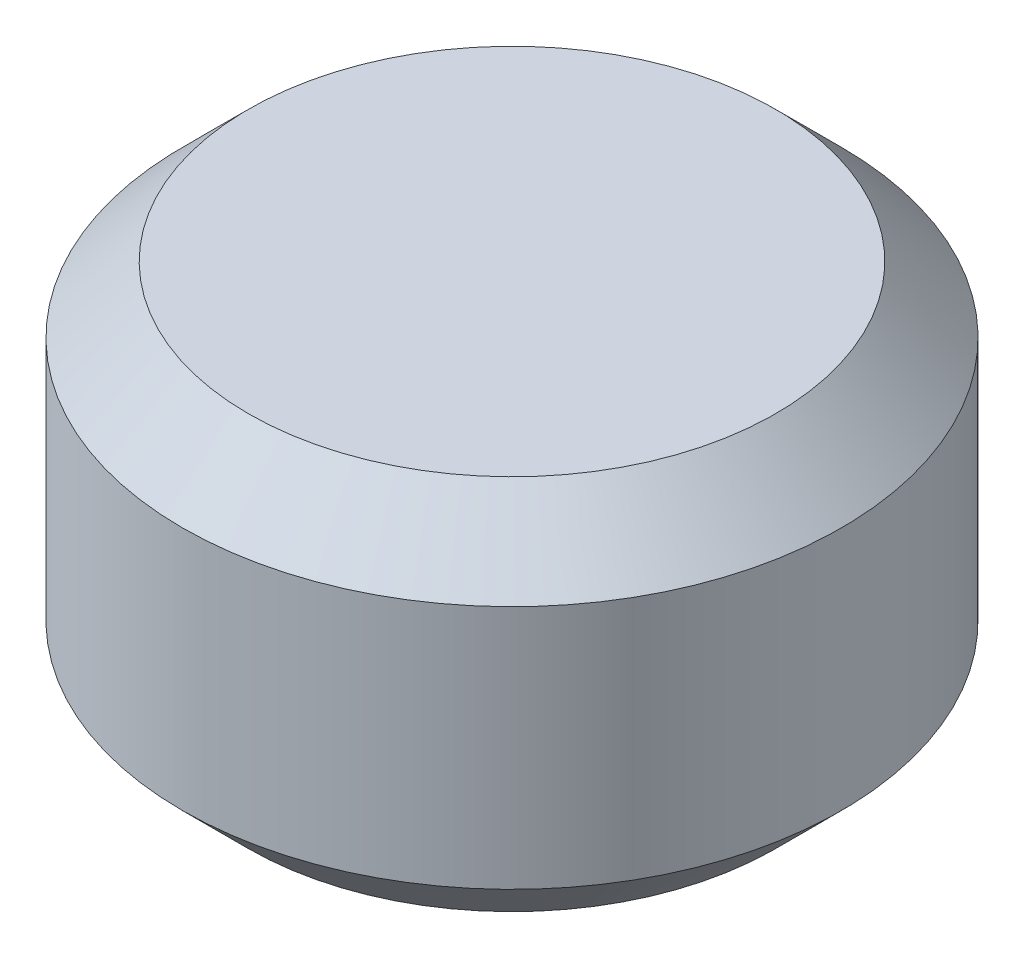
SolidWorks part; units mm, degrees
ref_plane "Front Plane" through (0, 0, 0) normal (0, 0, 1) x (1, 0, 0)
ref_plane "Top Plane" through (0, 0, 0) normal (0, 1, 0) x (1, 0, 0)
ref_plane "Right Plane" through (0, 0, 0) normal (1, 0, 0) x (0, 0, -1)
sketch "Sketch1" plane through (0, 0, 0) normal (0, 1, 0) x (1, 0, 0)
  circle A0 centre (0, 0) radius 1.75
  dimension "D1" = 3.5
extrude "Boss-Extrude1" add sketch "Sketch1" along normal blind 2
chamfer "Chamfer1" distance 0.35 angle 45 2 edges at (0, 0, 1.75) (0, 2, 1.75)
